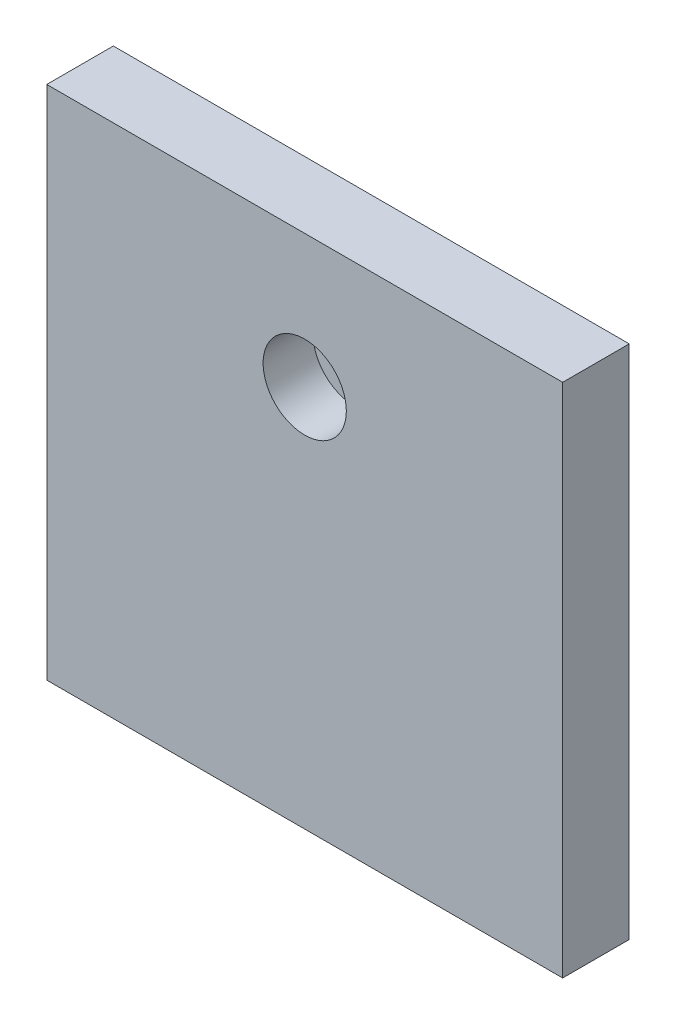
SolidWorks part; units mm, degrees
ref_plane "Alzado" through (0, 0, 0) normal (0, 0, 1) x (1, 0, 0)
ref_plane "Planta" through (0, 0, 0) normal (0, 1, 0) x (1, 0, 0)
ref_plane "Vista lateral" through (0, 0, 0) normal (1, 0, 0) x (0, 0, -1)
sketch "Croquis1" plane through (0, 0, 0) normal (0, 0, 1) x (1, 0, 0)
  line L0 (15.5, -8) -> (15.5, 0) construction
  line L1 (0, 0) -> (31, 0)
  line L2 (0, 0) -> (0, -31)
  line L3 (0, -31) -> (31, -31)
  line L4 (31, 0) -> (31, -31)
  circle A0 centre (15.5, -8) radius 1.25
  dimension "D4" = 2.5
  dimension "D1" = 31
  dimension "D2" = 31
  dimension "D3" = 8
extrude "Saliente-Extruir1" add sketch "Croquis1" along normal blind 4
sketch "Croquis2" plane through (0, 0, 4) normal (0, 0, 1) x (1, 0, 0)
  circle A0 centre (15.5, -8) radius 2.5
  dimension "D1" = 5
extrude "Cortar-Extruir1" cut sketch "Croquis2" against normal blind 3
